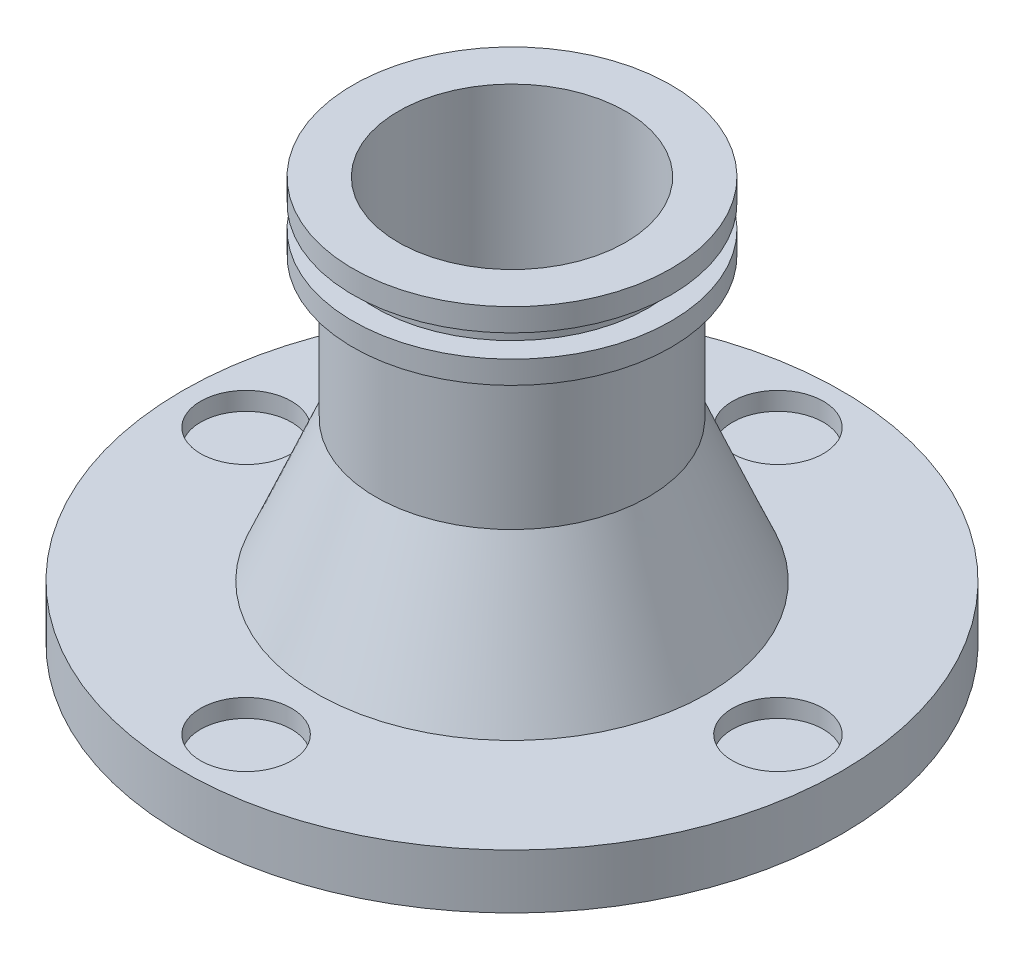
SolidWorks part; units mm, degrees
ref_plane "Front Plane" through (0, 0, 0) normal (0, 0, 1) x (1, 0, 0)
ref_plane "Top Plane" through (0, 0, 0) normal (0, 1, 0) x (1, 0, 0)
ref_plane "Right Plane" through (0, 0, 0) normal (1, 0, 0) x (0, 0, -1)
sketch "Sketch1" plane through (0, 0, 0) normal (0, 0, 1) x (1, 0, 0)
  line L0 (0, 0) -> (0, 89) construction
  line L1 (-25, 89) -> (-35, 89)
  line L2 (-35, 89) -> (-35, 84)
  line L3 (-35, 84) -> (-30, 84)
  line L4 (-30, 84) -> (-30, 79)
  line L5 (-30, 79) -> (-35, 79)
  line L6 (-35, 79) -> (-35, 74)
  line L7 (-35, 74) -> (-30, 74)
  line L8 (-30, 74) -> (-30, 43)
  line L9 (-30, 43) -> (-42.9767, 12)
  line L10 (-42.9767, 12) -> (-72.5, 12)
  line L11 (-72.5, 12) -> (-72.5, 0)
  line L12 (-72.5, 0) -> (-43, 0)
  line L13 (-43, 0) -> (-25, 43)
  line L14 (-25, 43) -> (-25, 89)
  dimension "D1" = 50
  dimension "D2" = 70
  dimension "D3" = 60
  dimension "D4" = 5
  dimension "D5" = 89
  dimension "D6" = 15
  dimension "D7" = 46
  dimension "D8" = 12
  dimension "D9" = 86
  dimension "D10" = 145
revolve "Revolve1" add sketch "Sketch1" angle 360 about L0
sketch "Sketch5" plane through (0, 12, 0) normal (0, 1, 0) x (1, 0, 0)
  circle A0 centre (0, 0) radius 58.5 construction
  circle A1 centre (0, 58.5) radius 10
  circle A2 centre (58.5, 0) radius 10
  circle A3 centre (0, -58.5) radius 10
  circle A4 centre (-58.5, 0) radius 10
  point P14 (0, 0)
  dimension "D1" = 117
  dimension "D2" = 20
  dimension "D3" = 4
extrude "Cut-Extrude1" cut sketch "Sketch5" against normal blind 4
